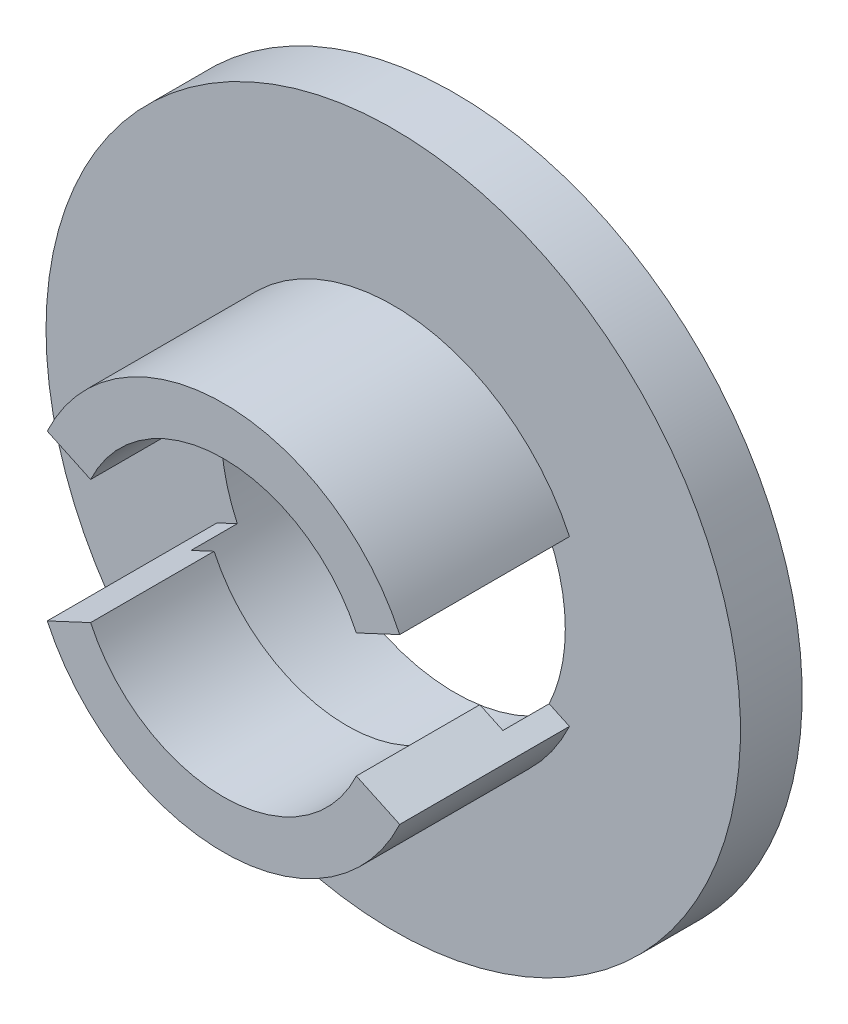
SolidWorks part; units mm, degrees
ref_plane "Plano frontal" through (0, 0, 0) normal (0, 0, 1) x (1, 0, 0)
ref_plane "Plano superior" through (0, 0, 0) normal (0, 1, 0) x (1, 0, 0)
ref_plane "Plano direito" through (0, 0, 0) normal (1, 0, 0) x (0, 0, -1)
sketch "Esboço1" plane through (0, 0, 0) normal (0, 0, 1) x (1, 0, 0)
  line L0 (18, 2.5) -> (13.9782, 2.5)
  line L1 (18, -2.5) -> (18, 2.5)
  line L2 (13.9782, -2.5) -> (18, -2.5)
  line L3 (2.5, -18) -> (2.5, -13.9782)
  line L4 (-2.5, -18) -> (2.5, -18)
  line L5 (-2.5, -13.9782) -> (-2.5, -18)
  line L6 (-18, -2.5) -> (-13.9782, -2.5)
  line L7 (-18, 2.5) -> (-18, -2.5)
  line L8 (-13.9782, 2.5) -> (-18, 2.5)
  line L9 (-2.5, 18) -> (-2.5, 13.9782)
  line L10 (2.5, 18) -> (-2.5, 18)
  line L11 (2.5, 13.9782) -> (2.5, 18)
  circle A0 centre (0, 0) radius 11.15
  circle A1 centre (0, 0) radius 6.1
  circle A3 centre (0, 0) radius 4.3
  arc A4 (-13.9782, -2.5) -> (-2.5, -13.9782) centre (0, 0) ccw
  arc A5 (13.9782, 2.5) -> (2.5, 13.9782) centre (0, 0) ccw
  arc A6 (2.5, -13.9782) -> (13.9782, -2.5) centre (0, 0) ccw
  arc A7 (-13.9782, -2.5) -> (-2.5, -13.9782) centre (0, 0) ccw
  arc A8 (-2.5, 13.9782) -> (-13.9782, 2.5) centre (0, 0) ccw
  arc A9 (-2.5, 13.9782) -> (-13.9782, 2.5) centre (0, 0) ccw
  arc A10 (13.9782, 2.5) -> (2.5, 13.9782) centre (0, 0) ccw
  arc A11 (2.5, -13.9782) -> (13.9782, -2.5) centre (0, 0) ccw
  dimension "D1" = 28.4
  dimension "D2" = 8.6
  dimension "D3" = 12.2
  dimension "D5" = 22.3
  dimension "D6" = 14.2
  dimension "D7" = 14.2
  dimension "D8" = 14.2
  dimension "D9" = 14.2
  dimension "D10" = 2.5
  dimension "D11" = 2.5
  dimension "D12" = 13.9782
  dimension "D13" = 13.9782
  dimension "D14" = 18
  dimension "D15" = 18
  dimension "D16" = 2.5
  dimension "D17" = 2.5
  dimension "D18" = 13.9782
  dimension "D19" = 13.9782
  dimension "D20" = 18
  dimension "D21" = 18
  dimension "D22" = 2.5
  dimension "D23" = 2.5
  dimension "D24" = 13.9782
  dimension "D25" = 13.9782
  dimension "D26" = 18
  dimension "D27" = 18
  dimension "D28" = 2.5
  dimension "D29" = 2.5
  dimension "D30" = 13.9782
  dimension "D31" = 13.9782
  dimension "D32" = 18
  dimension "D33" = 18
extrude "Ressalto-extrusão1" add sketch "Esboço1" along normal blind 15 contours L9 A8 L8 L7 L6 A4 L5 L4 L3 A6 L2 L1 L0 A5 L11 L10 A0
sketch "Esboço2" plane through (0, 0, 0) normal (0, 0, -1) x (-1, 0, 0)
  line L4 (2.5, 18) -> (2.5, 13.9782) construction
  line L5 (-2.5, 18) -> (2.5, 18) construction
  circle A0 centre (0, 0) radius 22.5
  arc A9 (2.5, 13.9782) -> (-13.9782, -2.5) centre (0, 0) ccw
  arc A10 (-13.9782, -2.5) -> (2.5, -13.9782) centre (0, 0) ccw
  arc A11 (-2.5, -13.9782) -> (13.9782, -2.5) centre (0, 0) ccw
  arc A12 (13.9782, -2.5) -> (2.5, 13.9782) centre (0, 0) ccw
  line M18 (2.5, 13.9782) -> (2.5, 18)
  line M19 (2.5, 18) -> (-2.5, 18)
  line M20 (-2.5, 18) -> (-2.5, 13.9782)
  arc M21 (-2.5, 13.9782) -> (-13.9782, 2.5) centre (0, 0) ccw
  line M22 (-13.9782, 2.5) -> (-18, 2.5)
  line M23 (-18, 2.5) -> (-18, -2.5)
  line M24 (-18, -2.5) -> (-13.9782, -2.5)
  arc M25 (-13.9782, -2.5) -> (-2.5, -13.9782) centre (0, 0) ccw
  line M26 (-2.5, -13.9782) -> (-2.5, -18)
  line M27 (-2.5, -18) -> (2.5, -18)
  line M28 (2.5, -18) -> (2.5, -13.9782)
  arc M29 (2.5, -13.9782) -> (13.9782, -2.5) centre (0, 0) ccw
  line M30 (13.9782, -2.5) -> (18, -2.5)
  line M31 (18, -2.5) -> (18, 2.5)
  line M32 (18, 2.5) -> (13.9782, 2.5)
  arc M33 (13.9782, 2.5) -> (2.5, 13.9782) centre (0, 0) ccw
  dimension "D1" = 45
  dimension "D2" = 14.2
  dimension "D3" = 14.2
  dimension "D4" = 14.2
  dimension "D5" = 14.2
  dimension "D6" = 11.4782
  dimension "D7" = 2.5
  dimension "D8" = 5
  dimension "D9" = 16.4782
  dimension "D10" = 4.0218
  dimension "D11" = 18
  dimension "D12" = 31.9782
  dimension "D14" = 20.5
  dimension "D15" = 20.5
  dimension "D16" = 31.9782
extrude "Ressalto-extrusão2" add sketch "Esboço2" along normal blind 4 separate body contours A0 M18 M33 M32 M31 M30 M29 M28 M27 M26 M25 M24 M23 M22 M21 M20 M19 | A10 M26 M27 M28 | A9 M22 M23 M24 | A9 M18 M19 M20 | A12 M30 M31 M32
sketch "Esboço5" plane through (0, 0, 15) normal (0, 0, 1) x (1, 0, 0)
  circle A0 centre (0, 0) radius 11.15 construction
  circle A1 centre (0, 0) radius 11.15
  circle A2 centre (0, 0) radius 8
  dimension "D1" = 16
extrude "Ressalto-extrusão6" add sketch "Esboço5" against normal blind 8
sketch "Esboço7" plane through (0, 0, 0) normal (0, 0, -1) x (-1, 0, 0)
  circle A0 centre (0, 0) radius 11.15 construction
  circle A1 centre (0, 0) radius 14.2 construction
  circle A2 centre (0, 0) radius 11.15
  circle A3 centre (0, 0) radius 14.2
extrude "Ressalto-extrusão7" add sketch "Esboço7" along normal up to surface (4 mm away) up to face at (-14.2, 0, -4)
sketch "Esboço8" plane through (0, 0, 7) normal (0, 0, -1) x (-1, 0, 0)
  circle A0 centre (0, 0) radius 8 construction
  circle A1 centre (0, 0) radius 11.15 construction
  circle A2 centre (0, 0) radius 8
  circle A3 centre (0, 0) radius 11.15
extrude "Ressalto-extrusão8" add sketch "Esboço8" along normal blind 4
sketch "Esboço9" plane through (0, 0, 15) normal (0, 0, 1) x (1, 0, 0)
  line L0 (2.5, -18) -> (2.5, -13.9782) construction
  line L1 (-2.5, -18) -> (2.5, -18) construction
  line L2 (-11.4195, 5.325) -> (-8.6099, 4.0149)
  line L4 (-11.4195, -5.325) -> (-8.6099, -4.0149)
  line L7 (8.6099, -4.0149) -> (11.4195, -5.325)
  line L8 (8.6099, 4.0149) -> (11.4195, 5.325)
  arc A0 (-8.6099, -4.0149) -> (8.6099, -4.0149) centre (0, 0) ccw
  arc A6 (8.6099, 4.0149) -> (-8.6099, 4.0149) centre (0, 0) ccw
  arc A7 (11.4195, 5.325) -> (-11.4195, 5.325) centre (0, 0) ccw
  arc A15 (-11.4195, -5.325) -> (11.4195, -5.325) centre (0, 0) ccw
  dimension "D2" = 25.2
  dimension "D3" = 2.5
  dimension "D4" = 4.0218
  dimension "D5" = 4.0218
  dimension "D1" = 19
  dimension "D6" = 18
extrude "Ressalto-extrusão9" add sketch "Esboço9" along normal blind 7
sketch "Esboço10" plane through (0, 0, 15) normal (0, 0, 1) x (1, 0, 0)
  line L0 (11.4195, -5.325) -> (8.6099, -4.0149) construction
  line L1 (-8.6099, -4.0149) -> (-11.4195, -5.325) construction
  line L2 (8.6099, 4.0149) -> (11.4195, 5.325) construction
  line L3 (-11.4195, 5.325) -> (-8.6099, 4.0149) construction
  line L4 (11.4195, -5.325) -> (8.6099, -4.0149)
  line L5 (-8.6099, -4.0149) -> (-11.4195, -5.325)
  line L6 (8.6099, 4.0149) -> (11.4195, 5.325)
  line L7 (-11.4195, 5.325) -> (-8.6099, 4.0149)
  line L12 (-2.5, 18) -> (-2.5, 13.9782)
  line L13 (-13.9782, 2.5) -> (-18, 2.5)
  line L14 (-18, 2.5) -> (-18, -2.5)
  line L15 (-18, -2.5) -> (-13.9782, -2.5)
  line L16 (-2.5, -13.9782) -> (-2.5, -18)
  line L17 (-2.5, -18) -> (2.5, -18)
  line L18 (2.5, -18) -> (2.5, -13.9782)
  line L19 (13.9782, -2.5) -> (18, -2.5)
  line L20 (18, -2.5) -> (18, 2.5)
  line L21 (18, 2.5) -> (13.9782, 2.5)
  line L22 (2.5, 13.9782) -> (2.5, 18)
  line L23 (2.5, 18) -> (-2.5, 18)
  line L24 (-2.5, 18) -> (-2.5, 13.9782)
  line L25 (-13.9782, 2.5) -> (-18, 2.5)
  line L26 (-18, 2.5) -> (-18, -2.5)
  line L27 (-18, -2.5) -> (-13.9782, -2.5)
  line L28 (-2.5, -13.9782) -> (-2.5, -18)
  line L29 (-2.5, -18) -> (2.5, -18)
  line L30 (2.5, -18) -> (2.5, -13.9782)
  line L31 (13.9782, -2.5) -> (18, -2.5)
  line L32 (18, -2.5) -> (18, 2.5)
  line L33 (18, 2.5) -> (13.9782, 2.5)
  line L34 (2.5, 13.9782) -> (2.5, 18)
  line L35 (2.5, 18) -> (-2.5, 18)
  arc A0 (-11.4195, -5.325) -> (11.4195, -5.325) centre (0, 0) ccw construction
  arc A1 (-8.6099, -4.0149) -> (8.6099, -4.0149) centre (0, 0) ccw construction
  arc A2 (8.6099, 4.0149) -> (-8.6099, 4.0149) centre (0, 0) ccw construction
  arc A3 (11.4195, 5.325) -> (-11.4195, 5.325) centre (0, 0) ccw construction
  arc A4 (-2.5, 13.9782) -> (-13.9782, 2.5) centre (0, 0) ccw
  arc A5 (-13.9782, -2.5) -> (-2.5, -13.9782) centre (0, 0) ccw
  arc A6 (2.5, -13.9782) -> (13.9782, -2.5) centre (0, 0) ccw
  arc A7 (13.9782, 2.5) -> (2.5, 13.9782) centre (0, 0) ccw
  arc A8 (-2.5, 13.9782) -> (-13.9782, 2.5) centre (0, 0) ccw
  arc A9 (-13.9782, -2.5) -> (-2.5, -13.9782) centre (0, 0) ccw
  arc A10 (2.5, -13.9782) -> (13.9782, -2.5) centre (0, 0) ccw
  arc A11 (13.9782, 2.5) -> (2.5, 13.9782) centre (0, 0) ccw
  arc A12 (-11.4195, -5.325) -> (11.4195, -5.325) centre (0, 0) ccw
  arc A13 (-8.6099, -4.0149) -> (8.6099, -4.0149) centre (0, 0) ccw
  arc A14 (8.6099, 4.0149) -> (-8.6099, 4.0149) centre (0, 0) ccw
  arc A15 (11.4195, 5.325) -> (-11.4195, 5.325) centre (0, 0) ccw
  dimension "D1" = 0
extrude "Corte-extrusão2" cut sketch "Esboço10" against normal up to surface (15 mm away) up to face at (-22.5, 0, 0)
sketch "Esboço11" plane through (0, 0, 22) normal (0, 0, 1) x (1, 0, 0)
  line L0 (11.4195, -5.325) -> (8.6099, -4.0149) construction
  line L1 (-8.6099, -4.0149) -> (-11.4195, -5.325) construction
  line L2 (8.6099, 4.0149) -> (11.4195, 5.325) construction
  line L3 (-11.4195, 5.325) -> (-8.6099, 4.0149) construction
  line L4 (11.4195, -5.325) -> (8.6099, -4.0149)
  line L5 (-8.6099, -4.0149) -> (-11.4195, -5.325)
  line L6 (8.6099, 4.0149) -> (11.4195, 5.325)
  line L7 (-11.4195, 5.325) -> (-8.6099, 4.0149)
  arc A0 (-11.4195, -5.325) -> (11.4195, -5.325) centre (0, 0) ccw construction
  arc A1 (-8.6099, -4.0149) -> (8.6099, -4.0149) centre (0, 0) ccw construction
  arc A2 (8.6099, 4.0149) -> (-8.6099, 4.0149) centre (0, 0) ccw construction
  arc A3 (11.4195, 5.325) -> (-11.4195, 5.325) centre (0, 0) ccw construction
  arc A4 (-11.4195, -5.325) -> (11.4195, -5.325) centre (0, 0) ccw
  arc A5 (-8.6099, -4.0149) -> (8.6099, -4.0149) centre (0, 0) ccw
  arc A6 (8.6099, 4.0149) -> (-8.6099, 4.0149) centre (0, 0) ccw
  arc A7 (11.4195, 5.325) -> (-11.4195, 5.325) centre (0, 0) ccw
extrude "Corte-extrusão3" cut sketch "Esboço11" against normal blind 11
